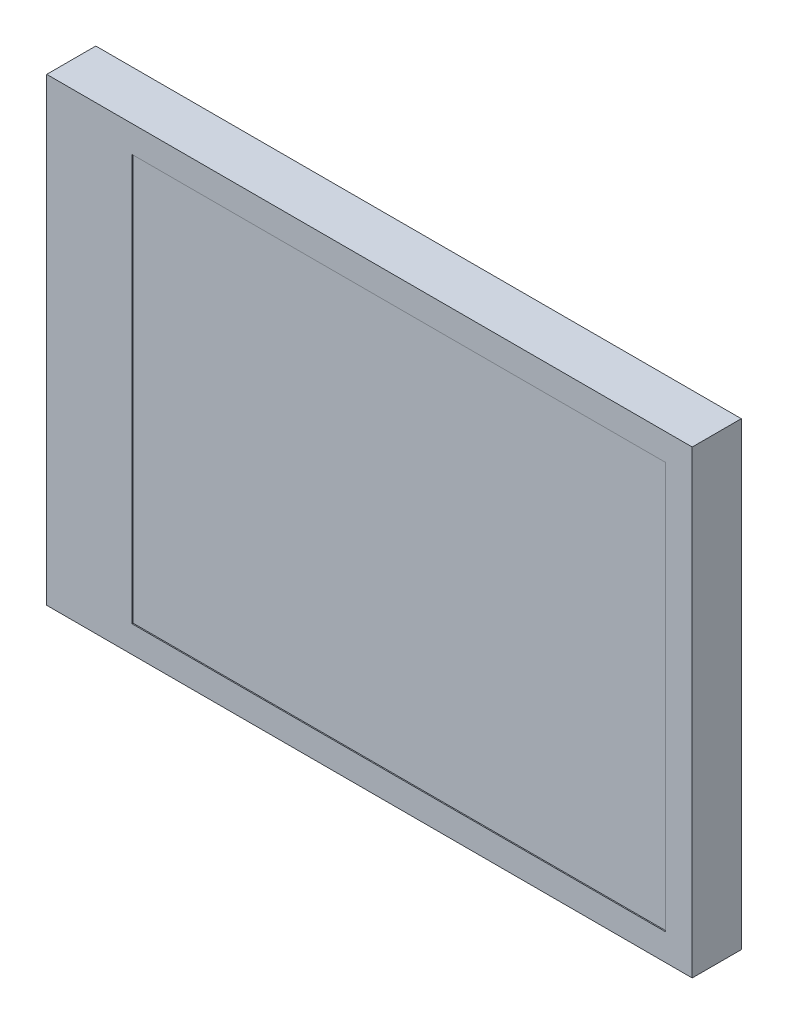
SolidWorks part; units mm, degrees
ref_plane "Plan de face" through (0, 0, 0) normal (0, 0, 1) x (1, 0, 0)
ref_plane "Plan de dessus" through (0, 0, 0) normal (0, 1, 0) x (1, 0, 0)
ref_plane "Plan de droite" through (0, 0, 0) normal (1, 0, 0) x (0, 0, -1)
sketch "Esquisse1" plane through (0, 0, 0) normal (0, 0, 1) x (1, 0, 0)
  line L1 (-30.25, -21.55) -> (30.25, -21.55)
  line L2 (-30.25, -21.55) -> (-30.25, 21.55)
  line L3 (-30.25, 21.55) -> (30.25, 21.55)
  line L4 (30.25, -21.55) -> (30.25, 21.55)
  line L5 (-30.25, -21.55) -> (30.25, 21.55) construction
  line L6 (-30.25, 21.55) -> (30.25, -21.55) construction
  point P0 (0, 0)
  dimension "D1" = 43.1
  dimension "D2" = 60.5
extrude "Boss.-Extru.1" add sketch "Esquisse1" along normal blind 4.6
sketch "Esquisse2" plane through (0, 0, 4.6) normal (0, 0, 1) x (1, 0, 0)
  line L0 (30.25, 21.55) -> (-30.25, 21.55) construction
  line L1 (-22.25, 19.05) -> (27.75, 19.05)
  line L2 (-22.25, 19.05) -> (-22.25, -19.05)
  line L3 (-22.25, -19.05) -> (27.75, -19.05)
  line L4 (27.75, 19.05) -> (27.75, -19.05)
  line L5 (30.25, -21.55) -> (30.25, 21.55) construction
  line L6 (-30.25, -21.55) -> (30.25, -21.55) construction
  line L7 (-30.25, 21.55) -> (-30.25, -21.55) construction
  dimension "D1" = 2.5
  dimension "D2" = 2.5
  dimension "D3" = 2.5
  dimension "D4" = 8
extrude "Enlèv. mat.-Extru.1" cut sketch "Esquisse2" against normal blind 0.1
sketch "Esquisse3" plane through (0, 0, 0) normal (0, 0, -1) x (-1, 0, 0)
  line L0 (30.25, -21.55) -> (-30.25, -21.55) construction
  line L1 (20.75, -21.55) -> (28.25, -21.55)
  line L2 (20.75, -21.55) -> (20.75, -16.25)
  line L3 (20.75, -16.25) -> (28.25, -16.25)
  line L4 (28.25, -21.55) -> (28.25, -16.25)
  line L5 (30.25, 21.55) -> (30.25, -21.55) construction
  dimension "D1" = 7.5
  dimension "D2" = 5.3
  dimension "D3" = 2
extrude "Boss.-Extru.2" add sketch "Esquisse3" along normal blind 2.5 separate body
sketch "Esquisse4" plane through (0, 0, 0) normal (0, 0, -1) x (-1, 0, 0)
  line L0 (30.25, 21.55) -> (30.25, -21.55) construction
  line L1 (30.25, 14.65) -> (24.65, 14.65)
  line L2 (30.25, 14.65) -> (30.25, -2.95)
  line L3 (30.25, -2.95) -> (24.65, -2.95)
  line L4 (24.65, 14.65) -> (24.65, -2.95)
  line L5 (-30.25, 21.55) -> (30.25, 21.55) construction
  dimension "D1" = 17.6
  dimension "D2" = 5.6
  dimension "D3" = 6.9
extrude "Boss.-Extru.3" add sketch "Esquisse4" along normal blind 4.1 separate body
sketch "Esquisse5" plane through (0, 0, 0) normal (0, 0, -1) x (-1, 0, 0)
  line L0 (30.25, -21.55) -> (-30.25, -21.55) construction
  line L1 (-28.25, -21.55) -> (-13.45, -21.55)
  line L2 (-28.25, -21.55) -> (-28.25, -6.25)
  line L3 (-28.25, -6.25) -> (-13.45, -6.25)
  line L4 (-13.45, -21.55) -> (-13.45, -6.25)
  line L5 (-30.25, -21.55) -> (-30.25, 21.55) construction
  dimension "D1" = 14.8
  dimension "D2" = 15.3
  dimension "D3" = 2
extrude "Boss.-Extru.4" add sketch "Esquisse5" along normal blind 2 separate body
